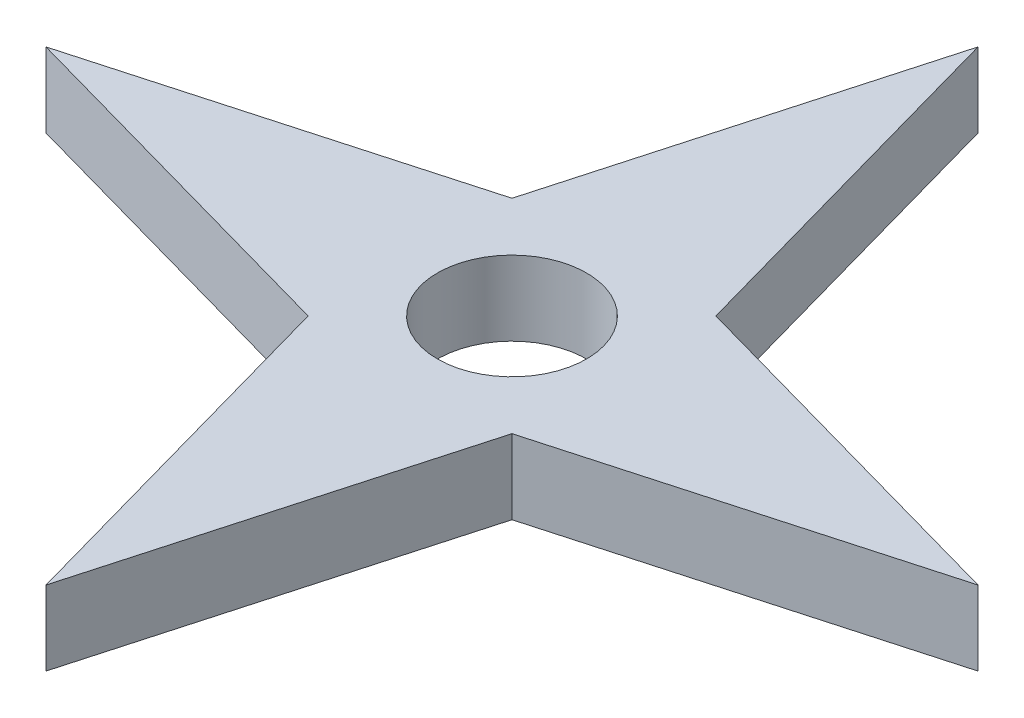
SolidWorks part; units mm, degrees
ref_plane "Front Plane" through (0, 0, 0) normal (0, 0, 1) x (1, 0, 0)
ref_plane "Top Plane" through (0, 0, 0) normal (0, 1, 0) x (1, 0, 0)
ref_plane "Right Plane" through (0, 0, 0) normal (1, 0, 0) x (0, 0, -1)
sketch "Sketch1" plane through (0, 0, 0) normal (0, 1, 0) x (1, 0, 0)
  line L0 (125, 0) -> (27.3437, 27.3438)
  line L11 (125, 0) -> (27.3437, -27.3437)
  line L12 (-27.3437, 27.3438) -> (-125, 0)
  line L13 (-27.3437, -27.3437) -> (-125, 0)
  line L16 (0, -125) -> (27.3437, -27.3437)
  line L23 (0, -125) -> (-27.3437, -27.3437)
  line L24 (27.3437, 27.3438) -> (0, 125)
  line L25 (-27.3437, 27.3438) -> (0, 125)
  circle A0 centre (0, 0) radius 20
  point P0 (0, 0)
  point P1 (0, 0)
  point P4 (0, 0)
  point P8 (0, 0)
  point P18 (-125, -14.6464)
  point P25 (-119.928, -11.2002)
  point P151 (0, 0)
  point P397 (0, 0)
extrude "Boss-Extrude2" add sketch "Sketch1" along normal blind 20 contours A0 | L23 L13 L12 L25 L24 L0 L11 L16
